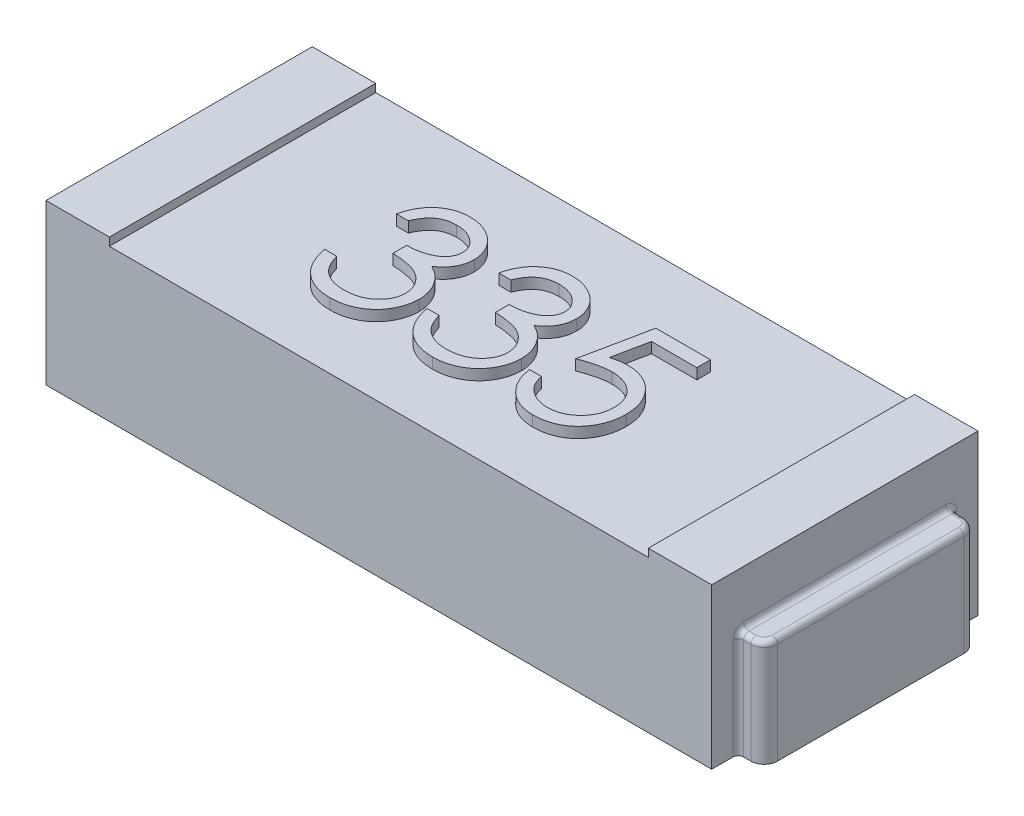
SolidWorks part; units mm, degrees
ref_plane "Plan de face" through (0, 0, 0) normal (0, 0, 1) x (1, 0, 0)
ref_plane "Plan de dessus" through (0, 0, 0) normal (0, 1, 0) x (1, 0, 0)
ref_plane "Plan de droite" through (0, 0, 0) normal (1, 0, 0) x (0, 0, -1)
sketch "Esquisse1" plane through (0, 0, 0) normal (0, 1, 0) x (1, 0, 0)
  line L1 (1.25, -0.5) -> (-1.25, -0.5)
  line L2 (1.25, -0.5) -> (1.25, 0.5)
  line L3 (1.25, 0.5) -> (-1.25, 0.5)
  line L4 (-1.25, -0.5) -> (-1.25, 0.5)
  line L5 (1.25, -0.5) -> (-1.25, 0.5) construction
  line L6 (1.25, 0.5) -> (-1.25, -0.5) construction
  point P0 (0, 0)
  dimension "D1" = 2.5
  dimension "D2" = 1
extrude "Boss.-Extru.1" add sketch "Esquisse1" along normal blind 0.6
sketch "Esquisse2" plane through (0, 0.6, 0) normal (0, 1, 0) x (1, 0, 0)
  line L0 (1.25, 0.5) -> (-1.25, 0.5) construction
  line L1 (1.0118, -0.5) -> (-1.0118, -0.5)
  line L2 (1.0118, -0.5) -> (1.0118, 0.5)
  line L3 (1.0118, 0.5) -> (-1.0118, 0.5)
  line L4 (-1.0118, -0.5) -> (-1.0118, 0.5)
  line L5 (1.0118, -0.5) -> (-1.0118, 0.5) construction
  line L6 (1.0118, 0.5) -> (-1.0118, -0.5) construction
  point P0 (0, 0)
extrude "Enlèv. mat.-Extru.1" cut sketch "Esquisse2" against normal blind 0.03
sketch "Esquisse3" plane through (0, 0, 0) normal (0, 1, 0) x (1, 0, 0)
  line L0 (1.25, -0.5) -> (1.25, 0.5) construction
  line L1 (1.25, 0.4) -> (1.2971, 0.4)
  line L2 (1.25, 0.4) -> (1.25, -0.4)
  line L3 (1.25, -0.4) -> (1.2971, -0.4)
  line L4 (1.3471, 0.35) -> (1.3471, -0.35)
  line L5 (1.25, 0.5) -> (1.0118, 0.5) construction
  line L6 (1.0118, -0.5) -> (1.25, -0.5) construction
  arc A0 (1.2971, -0.4) -> (1.3471, -0.35) centre (1.2971, -0.35) ccw
  arc A1 (1.2971, 0.4) -> (1.3471, 0.35) centre (1.2971, 0.35) cw
  dimension "D1" = 0.05
  dimension "D2" = 0.1
  dimension "D3" = 0.1
extrude "Boss.-Extru.2" add sketch "Esquisse3" along normal blind 0.4
fillet "Congé1" radius 0.02 8 edges at (1.25, 0.2, -0.4) (1.25, 0.2, 0.4) (1.2736, 0.4, -0.4) (1.3325, 0.4, -0.3854) (1.3471, 0.4, 0) (1.3325, 0.4, 0.3854) (1.2736, 0.4, 0.4) (1.25, 0.4, 0)
mirror "Symétrie2" about plane through (0, 0, 0) normal (1, 0, 0) of "Congé1", "Boss.-Extru.2"
sketch "Esquisse4" plane through (0, 0.57, 0) normal (0, 1, 0) x (1, 0, 0)
  line L0 (0.7576, -0.2803) -> (-0.7576, -0.2803) construction
  text T0 "335\r\n" font "Century Gothic" height 0.5
  point P3 (0, -0.2803)
extrude "Boss.-Extru.3" add sketch "Esquisse4" along normal blind 0.04
